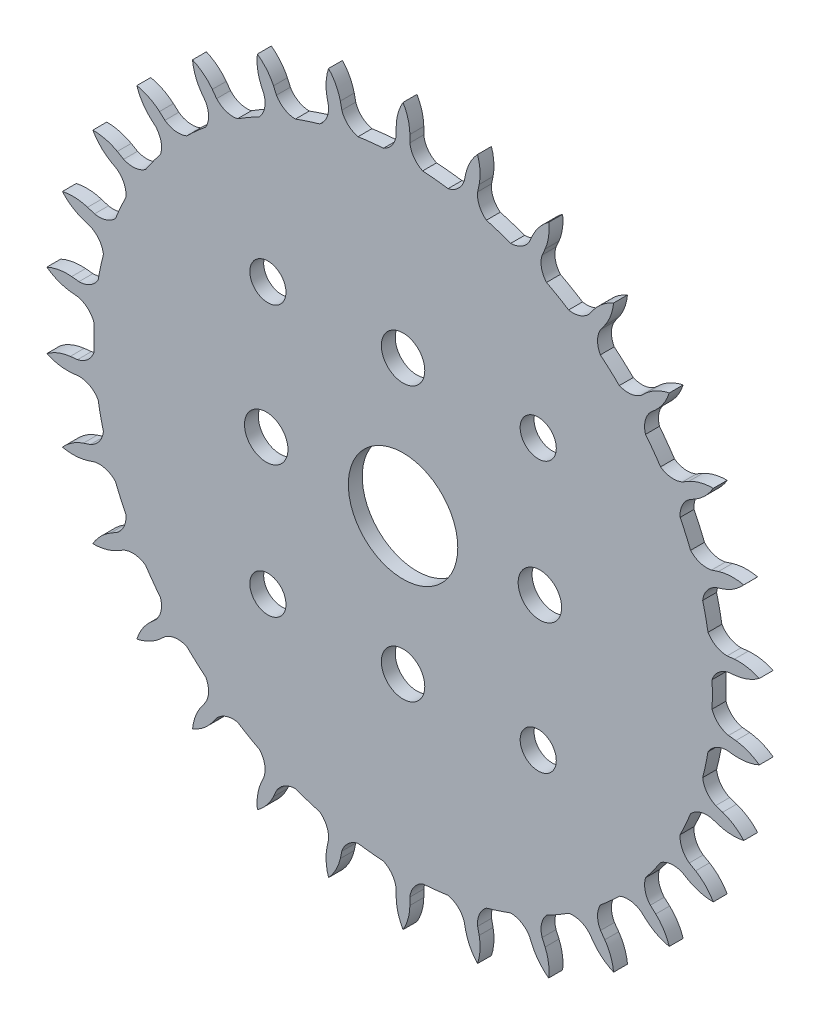
SolidWorks part; units mm, degrees
ref_plane "Front Plane" through (0, 0, 0) normal (0, 0, 1) x (1, 0, 0)
ref_plane "Top Plane" through (0, 0, 0) normal (0, 1, 0) x (1, 0, 0)
ref_plane "Right Plane" through (0, 0, 0) normal (1, 0, 0) x (0, 0, -1)
sketch "Sketch1" plane through (0, 0, 0) normal (0, 0, 1) x (1, 0, 0)
  circle A0 centre (0, 10) radius 1.5875
  circle A1 centre (0, 0) radius 22.6042
  circle A2 centre (9.8783, -9.8783) radius 1.3208
  circle A3 centre (9.8783, 9.8783) radius 1.3208
  circle A4 centre (-9.8783, -9.8783) radius 1.3208
  circle A5 centre (-9.8783, 9.8783) radius 1.3208
  circle A6 centre (0, 0) radius 4
  circle A7 centre (10, 0) radius 1.5875
  circle A8 centre (0, -10) radius 1.5875
  circle A9 centre (-10, 0) radius 1.5875
  dimension "D1" = 4
  dimension "D2" = 4
extrude "Boss-Extrude2" add sketch "Sketch1" along normal blind 1.016
sketch "Sketch2" plane through (0, 0, 1.016) normal (0, 0, 1) x (1, 0, 0)
  line L0 (-0.5, 23.868) -> (-0.5, 24.4014)
  line L1 (0.5, 23.868) -> (0.5, 24.4014)
  arc A0 (0.5, 24.4014) -> (0, 26.1794) centre (-3.159, 24.3318) ccw
  arc A1 (-0.5, 23.868) -> (-1.6391, 22.4794) centre (-2.1172, 24.0331) cw
  arc A2 (-0.5, 24.4014) -> (0, 26.1794) centre (3.159, 24.3318) cw
  arc A3 (0.5, 23.868) -> (1.6391, 22.4794) centre (2.1172, 24.0331) ccw
  arc A4 (-1.6391, 22.4794) -> (1.6391, 22.4794) centre (0, 28.2138) ccw
extrude "Boss-Extrude4" add sketch "Sketch2" against normal blind 1.016
pattern_circular "CirPattern1" count 30 over 360 about axis through (0, 0, 0) along (0, 0, 1) of "Boss-Extrude4"
